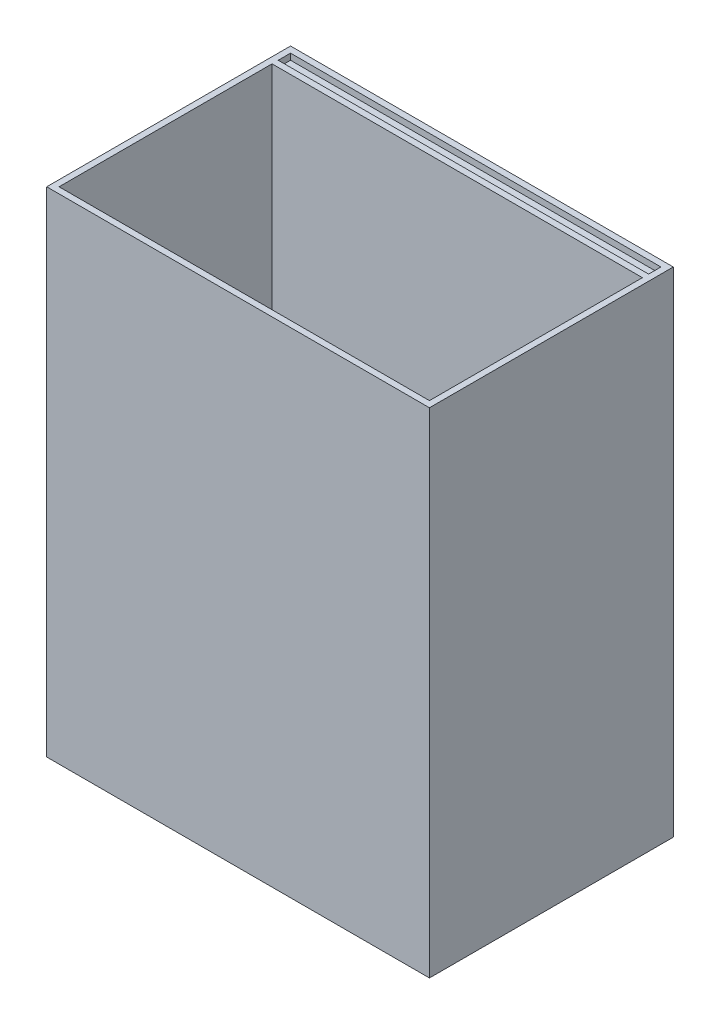
SolidWorks part; units mm, degrees
material "5086-H32, Rod (SS)"
ref_plane "Front Plane" through (0, 0, 0) normal (0, 0, 1) x (1, 0, 0)
ref_plane "Top Plane" through (0, 0, 0) normal (0, 1, 0) x (1, 0, 0)
ref_plane "Right Plane" through (0, 0, 0) normal (1, 0, 0) x (0, 0, -1)
sketch "Sketch1" plane through (0, 0, 0) normal (0, 0, 1) x (1, 0, 0)
  line L1 (0, 0) -> (6200, 0)
  line L2 (0, 0) -> (0, 8000)
  line L3 (0, 8000) -> (6200, 8000)
  line L4 (6200, 0) -> (6200, 8000)
  dimension "D1" = 6200
  dimension "D2" = 8000
extrude "Boss-Extrude1" add sketch "Sketch1" along normal blind 100
sketch "Sketch2" plane through (0, 0, 100) normal (0, 0, 1) x (1, 0, 0)
  line L0 (6200, 0) -> (6200, 8000) construction
  line L1 (0, 0) -> (6200, 0)
  line L2 (0, 0) -> (0, 100)
  line L3 (0, 100) -> (6200, 100)
  line L4 (6200, 0) -> (6200, 100)
  dimension "D1" = 6200
  dimension "D2" = 100
extrude "Boss-Extrude2" add sketch "Sketch2" along normal blind 3850
sketch "Sketch3" plane through (0, 0, 3950) normal (0, 0, 1) x (1, 0, 0)
  line L1 (0, 0) -> (6200, 0)
  line L2 (0, 0) -> (0, 8000)
  line L3 (0, 8000) -> (6200, 8000)
  line L4 (6200, 0) -> (6200, 8000)
  dimension "D1" = 8000
  dimension "D2" = 6200
extrude "Boss-Extrude3" add sketch "Sketch3" against normal blind 100
sketch "Sketch4" plane through (0, 0, 0) normal (0, 0, -1) x (-1, 0, 0)
sketch "Sketch5" plane through (6200, 0, 0) normal (1, 0, 0) x (0, 0, -1)
  line L1 (-3850, 100) -> (-100, 100)
  line L2 (-3850, 100) -> (-3850, 8000)
  line L3 (-3850, 8000) -> (-100, 8000)
  line L4 (-100, 100) -> (-100, 8000)
extrude "Boss-Extrude4" add sketch "Sketch5" against normal blind 100
sketch "Sketch6" plane through (0, 0, 0) normal (-1, 0, 0) x (0, 0, 1)
  line L1 (100, 100) -> (3850, 100)
  line L2 (100, 100) -> (100, 8000)
  line L3 (100, 8000) -> (3850, 8000)
  line L4 (3850, 100) -> (3850, 8000)
extrude "Boss-Extrude5" add sketch "Sketch6" against normal blind 100
sketch "Sketch8" plane through (0, 0, 3850) normal (0, 0, -1) x (-1, 0, 0)
  line L0 (-6100, 8000) -> (-6100, 100) construction
  line L1 (-6100, 1600) -> (0, 1600)
  line L2 (-6100, 1600) -> (-6100, 1401.7231)
  line L3 (-6100, 1401.7231) -> (0, 1401.7231)
  line L4 (0, 1600) -> (0, 1401.7231)
  line L5 (-100, 100) -> (-6100, 100) construction
  dimension "D1" = 1500
extrude "Boss-Extrude7" add sketch "Sketch8" along normal blind 3550
sketch "Sketch9" plane through (0, 1600, 0) normal (0, 1, 0) x (1, 0, 0)
  line L0 (6100, -300) -> (6100, -3850) construction
  line L1 (100, -300) -> (6100, -300)
  line L2 (100, -300) -> (100, -400)
  line L3 (100, -400) -> (6100, -400)
  line L4 (6100, -300) -> (6100, -400)
  dimension "D1" = 100
extrude "Boss-Extrude8" add sketch "Sketch9" along normal blind 6400
sketch "Sketch10" plane through (0, 0, 0) normal (0, -1, 0) x (1, 0, 0)
  line L5 (0, 3950) -> (0, 0) construction
  line L6 (0, 3575) -> (6200, 3575)
  line L7 (0, 3575) -> (0, 3475)
  line L8 (0, 3475) -> (6200, 3475)
  line L9 (6200, 3575) -> (6200, 3475)
  line L10 (6200, 3950) -> (6200, 0) construction
  line L11 (0, 3950) -> (6200, 3950) construction
  line L12 (0, 475) -> (6200, 475)
  line L13 (0, 475) -> (0, 375)
  line L14 (0, 375) -> (6200, 375)
  line L15 (6200, 475) -> (6200, 375)
  line L16 (0, 0) -> (6200, 0) construction
  dimension "D1" = 100
  dimension "D2" = 100
  dimension "D3" = 3000
  dimension "D4" = 475
  dimension "D5" = 475
extrude "Boss-Extrude9" add sketch "Sketch10" against normal blind 1500
sketch "Sketch11" plane through (0, 0, 0) normal (0, 0, -1) x (-1, 0, 0)
  line L0 (-6200, 0) -> (-6200, 8000) construction
  line L1 (-6200, 7900) -> (0, 7900)
  line L2 (-6200, 7900) -> (-6200, 7800)
  line L3 (-6200, 7800) -> (0, 7800)
  line L4 (0, 7900) -> (0, 7800)
  line L5 (0, 8000) -> (0, 0) construction
  line L6 (-6200, 8000) -> (0, 8000) construction
  line L7 (-6200, 5800) -> (0, 5800)
  line L8 (-6200, 5800) -> (-6200, 5700)
  line L9 (-6200, 5700) -> (0, 5700)
  line L10 (0, 5800) -> (0, 5700)
  line L12 (-6200, 5200) -> (0, 5200)
  line L13 (-6200, 5200) -> (-6200, 5100)
  line L14 (-6200, 5100) -> (0, 5100)
  line L15 (0, 5200) -> (0, 5100)
  dimension "D1" = 100
  dimension "D2" = 100
  dimension "D3" = 2000
  dimension "D4" = 100
  dimension "D5" = 100
  dimension "D6" = 500
extrude "Boss-Extrude11" add sketch "Sketch11" against normal blind 300
sketch "parachute location guide" plane through (0, 0, 0) normal (0, 0, -1) x (-1, 0, 0)
  line L0 (-3100, 8000) -> (-3100, 0) construction
  line L1 (-6200, 8000) -> (0, 8000)
  line L2 (-6200, 8000) -> (-6200, 0)
  line L3 (-6200, 0) -> (0, 0)
  line L4 (0, 8000) -> (0, 0)
  line L5 (-6200, 4000) -> (0, 4000) construction
  line L6 (-5700, 7500) -> (-5700, 8000) construction
  line L7 (-5700, 7500) -> (-5200, 7500)
  line L8 (-5700, 7500) -> (-5700, 7000)
  line L9 (-5700, 7000) -> (-5200, 7000)
  line L10 (-5200, 7500) -> (-5200, 7000)
  line L11 (-5700, 7500) -> (-6200, 7500) construction
  line L12 (-500, 7500) -> (-500, 8000) construction
  line L13 (-500, 7500) -> (0, 7500) construction
  line L14 (-500, 7000) -> (-1000, 7000)
  line L15 (-1000, 7500) -> (-1000, 7000)
  line L16 (-500, 7500) -> (-1000, 7500)
  line L17 (-500, 7500) -> (-500, 7000)
  line L18 (-5700, 500) -> (-5700, 0) construction
  line L19 (-5700, 500) -> (-6200, 500) construction
  line L20 (-5700, 1000) -> (-5200, 1000)
  line L21 (-5200, 500) -> (-5200, 1000)
  line L22 (-5700, 500) -> (-5200, 500)
  line L23 (-5700, 500) -> (-5700, 1000)
  line L24 (-500, 500) -> (-500, 0) construction
  line L25 (-500, 500) -> (0, 500) construction
  line L26 (-500, 500) -> (-500, 1000)
  line L27 (-500, 500) -> (-1000, 500)
  line L28 (-1000, 500) -> (-1000, 1000)
  line L29 (-500, 1000) -> (-1000, 1000)
  line L31 (-3350, 3750) -> (-2850, 3750)
  line L32 (-3350, 3750) -> (-3350, 4250)
  line L33 (-3350, 4250) -> (-2850, 4250)
  line L34 (-2850, 3750) -> (-2850, 4250)
  line L35 (-3350, 3750) -> (-2850, 4250) construction
  line L36 (-3350, 4250) -> (-2850, 3750) construction
  point P36 (-3100, 4000)
  dimension "D1" = 8000
  dimension "D2" = 6200
  dimension "D3" = 500
  dimension "D4" = 500
